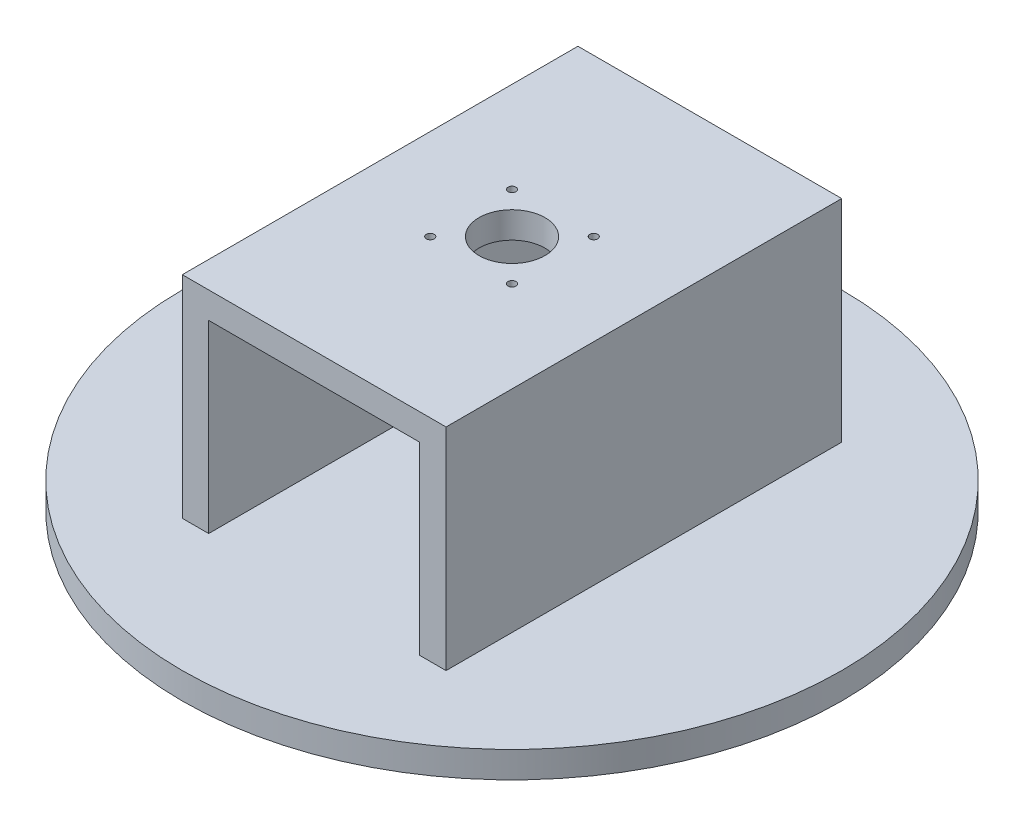
SolidWorks part; units mm, degrees
ref_plane "Front Plane" through (0, 0, 0) normal (0, 0, 1) x (1, 0, 0)
ref_plane "Top Plane" through (0, 0, 0) normal (0, 1, 0) x (1, 0, 0)
ref_plane "Right Plane" through (0, 0, 0) normal (1, 0, 0) x (0, 0, -1)
sketch "Sketch1" plane through (0, 0, 0) normal (0, 1, 0) x (1, 0, 0)
  circle A0 centre (0, 0) radius 125
  dimension "D1" = 250
extrude "Boss-Extrude1" add sketch "Sketch1" along normal blind 10
sketch "Sketch2" plane through (0, 10, 0) normal (0, 1, 0) x (1, 0, 0)
  line L1 (-50, 75) -> (50, 75)
  line L2 (-50, 75) -> (-50, -75)
  line L3 (-50, -75) -> (50, -75)
  line L4 (50, 75) -> (50, -75)
  line L5 (-50, 75) -> (50, -75) construction
  line L6 (-50, -75) -> (50, 75) construction
  line L7 (-40, 75) -> (40, 75)
  line L8 (-40, 75) -> (-40, -75)
  line L9 (-40, -75) -> (40, -75)
  line L10 (40, 75) -> (40, -75)
  line L11 (-40, 75) -> (40, -75) construction
  line L12 (-40, -75) -> (40, 75) construction
  point P0 (0, 0)
  point P6 (0, 0)
  dimension "D1" = 150
  dimension "D2" = 100
  dimension "D3" = 80
extrude "Boss-Extrude2" add sketch "Sketch2" along normal blind 70 contours L8 L1 L2 L3 | L1 L10 L3 L4
sketch "Sketch3" plane through (0, 80, 0) normal (0, 1, 0) x (1, 0, 0)
  line L1 (-50, 75) -> (50, 75)
  line L2 (-50, 75) -> (-50, -75)
  line L3 (-50, -75) -> (50, -75)
  line L4 (50, 75) -> (50, -75)
extrude "Boss-Extrude3" add sketch "Sketch3" along normal blind 10
sketch "Sketch4" plane through (0, 90, 0) normal (0, 1, 0) x (1, 0, 0)
  line L1 (-15.5, 15.5) -> (15.5, 15.5) construction
  line L2 (-15.5, 15.5) -> (-15.5, -15.5) construction
  line L3 (-15.5, -15.5) -> (15.5, -15.5) construction
  line L4 (15.5, 15.5) -> (15.5, -15.5) construction
  line L5 (-15.5, 15.5) -> (15.5, -15.5) construction
  line L6 (-15.5, -15.5) -> (15.5, 15.5) construction
  circle A0 centre (-15.5, 15.5) radius 1.5
  circle A1 centre (15.5, 15.5) radius 1.5
  circle A2 centre (-15.5, -15.5) radius 1.5
  circle A3 centre (15.5, -15.5) radius 1.5
  circle A4 centre (0, 0) radius 12.5
  point P0 (0, 0)
  dimension "D1" = 3
  dimension "D4" = 25
  dimension "D2" = 31
  dimension "D3" = 31
extrude "Cut-Extrude1" cut sketch "Sketch4" against normal blind 10
